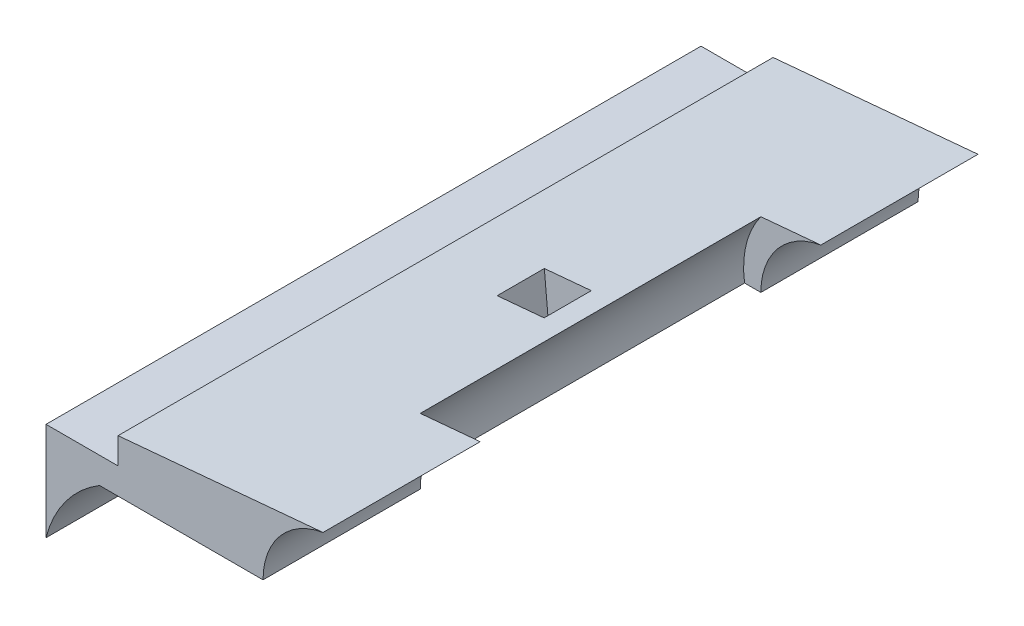
SolidWorks part; units mm, degrees
ref_plane "Alzado" through (0, 0, 0) normal (0, 0, 1) x (1, 0, 0)
ref_plane "Planta" through (0, 0, 0) normal (0, 1, 0) x (1, 0, 0)
ref_plane "Vista lateral" through (0, 0, 0) normal (1, 0, 0) x (0, 0, -1)
sketch "Croquis1" plane through (0, 0, 0) normal (0, 0, 1) x (1, 0, 0)
  line L0 (0, 0) -> (11, 0)
  line L1 (11, 0) -> (11, 4)
  line L3 (0, 0) -> (0, -4)
  line L4 (0, -4) -> (38.3431, -4)
  line L5 (11, 4) -> (44, 7)
  line L6 (44, 7) -> (44, 4)
  circle A0 centre (44, -2) radius 6 construction
  arc A1 (44, 4) -> (38.3431, -4) centre (44, -2) ccw
  dimension "D1" = 12
  dimension "D2" = 33
  dimension "D3" = 4
  dimension "D4" = 11
  dimension "D5" = 4
  dimension "D6" = 3
extrude "Saliente-Extruir1" add sketch "Croquis1" along normal blind 100
ref_plane "Plano1" through (0, 0, 50) normal (0, 0, 1) x (1, 0, 0)
sketch "Croquis3" plane through (0, 0, 50) normal (0, 0, 1) x (1, 0, 0)
  arc A0 (44, 4) -> (38.3431, -4) centre (44, -2) ccw construction
  arc A1 (44, 4) -> (38.3431, -4) centre (44, -2) ccw construction
  circle A2 centre (44, -2) radius 13.5
  dimension "D1" = 27
extrude "Cortar-Extruir2" cut sketch "Croquis3" against normal blind 26 and the other way blind 26
sketch "Croquis11" plane through (-0.2705, 2.9754, 0) normal (-0.0905, 0.9959, 0) x (0.9959, 0.0905, 0)
  line L0 (33.543, -24) -> (33.543, -76) construction
  line L1 (33.543, -50) -> (31.543, -50) construction
  line L3 (22.843, -46.4) -> (30.043, -46.4)
  line L4 (22.843, -46.4) -> (22.843, -53.6)
  line L5 (22.843, -53.6) -> (30.043, -53.6)
  line L6 (30.043, -46.4) -> (30.043, -53.6)
  line L7 (22.843, -46.4) -> (30.043, -53.6) construction
  line L8 (22.843, -53.6) -> (30.043, -46.4) construction
  point P6 (26.443, -50)
  dimension "D1" = 7.2
  dimension "D2" = 7.2
  dimension "D3" = 7
  dimension "D4" = 0
extrude "Cortar-Extruir6" cut sketch "Croquis11" against normal blind 6
sketch "Croquis12" plane through (0.2727, -2.9999, 0) normal (-0.0905, 0.9959, 0) x (0.9959, 0.0905, 0)
  line L0 (22.843, -46.4) -> (30.043, -53.6) construction
  line L2 (23.693, -52.75) -> (29.193, -52.75)
  line L3 (23.693, -52.75) -> (23.693, -47.25)
  line L4 (23.693, -47.25) -> (29.193, -47.25)
  line L5 (29.193, -52.75) -> (29.193, -47.25)
  line L6 (23.693, -52.75) -> (29.193, -47.25) construction
  line L7 (23.693, -47.25) -> (29.193, -52.75) construction
  point P4 (26.443, -50)
  dimension "D1" = 5.5
extrude "Cortar-Extruir7" cut sketch "Croquis12" against normal blind 6
sketch "Croquis13" plane through (-0.2705, 2.9754, 0) normal (-0.0905, 0.9959, 0) x (0.9959, 0.0905, 0)
  line L0 (33.543, -76) -> (33.543, -100) construction
  line L1 (44.4531, -100) -> (11.317, -100) construction
sketch "Croquis14" plane through (0, 0, 100) normal (0, 0, 1) x (1, 0, 0)
  line L0 (33.1347, 6.0122) -> (33.1347, -4) construction
  line L1 (0, -4) -> (38.3431, -4) construction
  arc A0 (33.1347, -4) -> (44, 7) centre (44.1356, -4) cw
extrude "Cortar-Extruir11" cut sketch "Croquis14" against normal through all and the other way through all flip side to cut
sketch "Croquis15" plane through (0, 0, 100) normal (0, 0, 1) x (1, 0, 0)
  line L0 (0, -4) -> (0, -15)
  line L1 (0, -4) -> (33.1347, -4) construction
  line L8 (42.2853, 6.8441) -> (11, 4)
  line L9 (11, 4) -> (11, 0)
  line L10 (11, 0) -> (0, 0)
  line L11 (0, 0) -> (0, -4)
  line L12 (0, -4) -> (33.1347, -4)
  line L17 (0, -4) -> (8.1699, -4)
  arc A0 (0, -15) -> (8.1699, -4) centre (17.5016, -19.4647) cw
  arc A2 (42.2853, 6.8441) -> (33.1347, -4) centre (44.1356, -4) ccw
  point P6 (8.1699, -4)
  dimension "D1" = 11
  dimension "D2" = 0
extrude "Saliente-Extruir2" add sketch "Croquis15" against normal up to surface (100 mm away) up to face at (15.9063, 0.7528, 0)
sketch "Croquis16" plane through (0, 0, 100) normal (0, 0, 1) x (1, 0, 0)
  line L0 (11, 0) -> (11, -4) construction
  line L1 (8.1699, -4) -> (33.1347, -4) construction
